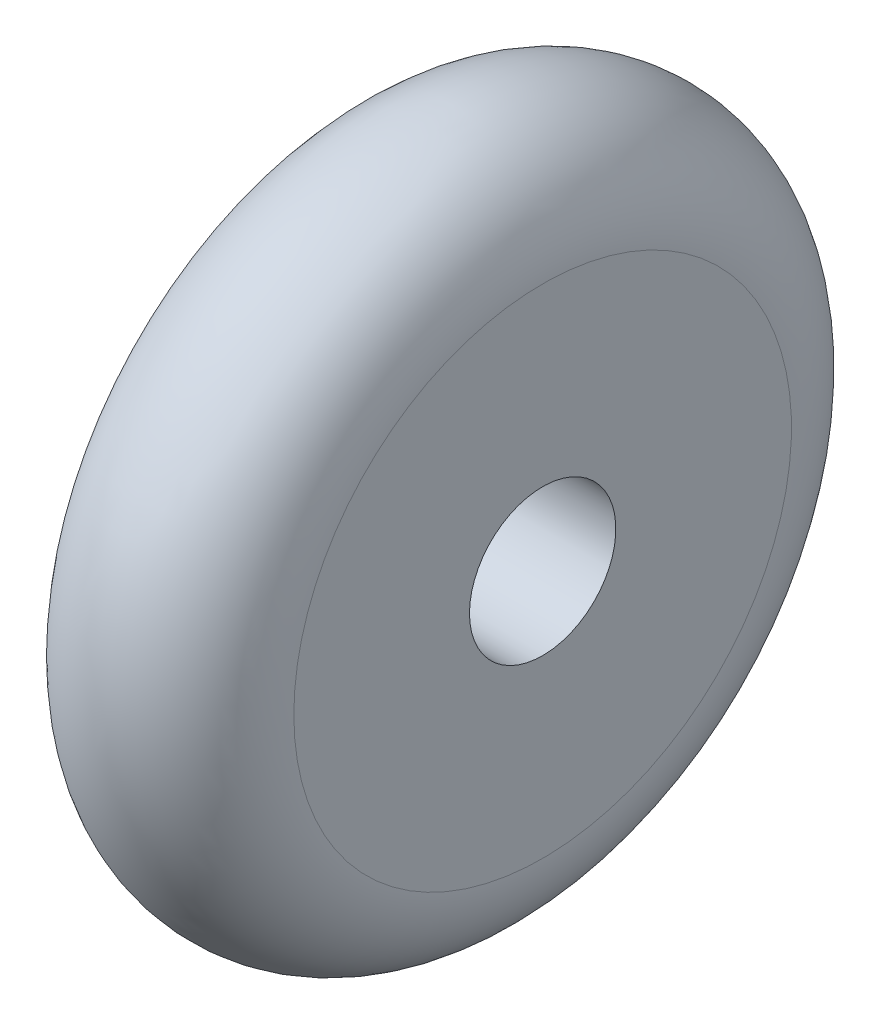
SolidWorks part; units mm, degrees
ref_plane "前视基准面" through (0, 0, 0) normal (0, 0, 1) x (1, 0, 0)
ref_plane "上视基准面" through (0, 0, 0) normal (0, 1, 0) x (1, 0, 0)
ref_plane "右视基准面" through (0, 0, 0) normal (1, 0, 0) x (0, 0, -1)
sketch "草图1" plane through (0, 0, 0) normal (0, 0, 1) x (1, 0, 0)
  line L0 (-3.5, 8.5) -> (-3.5, 0) construction
  line L1 (-3.5, 0) -> (3.5, 0) construction
  line L2 (3.5, 0) -> (3.5, 8.5) construction
  line L3 (-3.5, 2.5) -> (3.5, 2.5)
  line L4 (-3.5, 8.5) -> (-3.5, 2.5)
  line L5 (3.5, 8.5) -> (3.5, 2.5)
  arc A0 (-3.5, 8.5) -> (3.5, 8.5) centre (0, 8.5) cw
  dimension "D1" = 3.5
  dimension "D2" = 8.5
  dimension "D3" = 2.5
revolve "旋转1" add sketch "草图1" angle 360 about L1
